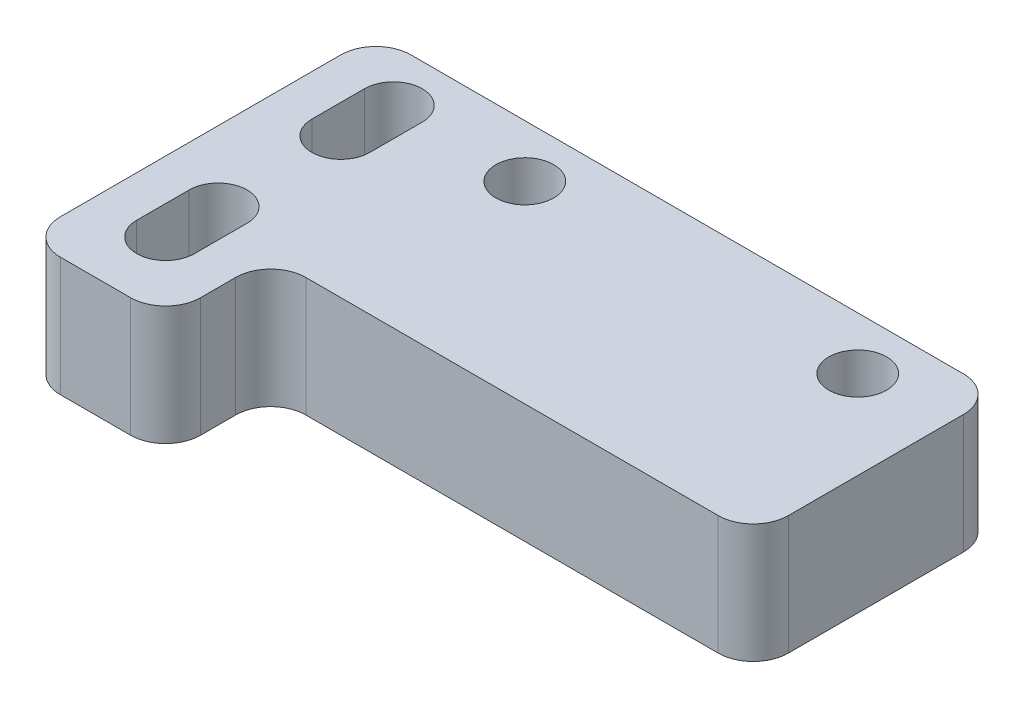
SolidWorks part; units mm, degrees
ref_plane "Front Plane" through (0, 0, 0) normal (0, 0, 1) x (1, 0, 0)
ref_plane "Top Plane" through (0, 0, 0) normal (0, 1, 0) x (1, 0, 0)
ref_plane "Right Plane" through (0, 0, 0) normal (1, 0, 0) x (0, 0, -1)
sketch "Sketch1" plane through (0, 0, 0) normal (0, 0, 1) x (1, 0, 0)
  line L0 (0, 3.6) -> (0, 0) construction
  line L1 (-13.77, -3.4) -> (13.77, -3.4)
  line L2 (-13.77, -3.4) -> (-13.77, 3.4)
  line L3 (-13.77, 3.4) -> (13.77, 3.4)
  line L4 (13.77, -3.4) -> (13.77, 3.4)
  line L5 (-13.77, -3.4) -> (13.77, 3.4) construction
  line L6 (-13.77, 3.4) -> (13.77, -3.4) construction
  circle A0 centre (0, 3.6) radius 7.6 construction
  point P0 (0, 0)
  dimension "D3" = 15.2
  dimension "D1" = 7
  dimension "D2" = 0.2
  dimension "D4" = 27.54
extrude "Boss-Extrude1" add sketch "Sketch1" along normal blind 8 contours A0 L3 L2 L1 L4
sketch "Sketch4" plane through (0, 0, 0) normal (0, 0, -1) x (-1, 0, 0)
  line L8 (-13.77, -3.4) -> (13.77, -3.4)
  line L9 (13.77, -3.4) -> (13.77, 3.4)
  line L10 (13.77, 3.4) -> (-13.77, 3.4)
  line L11 (-13.77, 3.4) -> (-13.77, -3.4)
  line L12 (-13.77, -3.4) -> (13.77, -3.4)
  line L13 (13.77, -3.4) -> (13.77, 3.4)
  line L14 (13.77, 3.4) -> (-13.77, 3.4)
  line L15 (-13.77, 3.4) -> (-13.77, -3.4)
  dimension "D1" = 0
extrude "Boss-Extrude2" add sketch "Sketch4" along normal blind 6
sketch "Sketch3" plane through (0, -3.4, 0) normal (0, -1, 0) x (1, 0, 0)
  line L0 (8.73, -3) -> (-10.27, -3) construction
  line L1 (13.77, -6) -> (-13.77, -6) construction
  line L2 (-13.77, 8) -> (-13.77, -6) construction
  arc A2 (7.13, 1) -> (10.33, 1) centre (8.73, -3) ccw construction
  arc A3 (-11.6208, 1) -> (-8.8261, 0.9674) centre (-10.27, -3) ccw construction
  circle A4 centre (8.73, -3) radius 1.65
  circle A5 centre (-10.27, -3) radius 1.65
  dimension "D1" = 3.3
  dimension "D2" = 19
  dimension "D3" = 3
  dimension "D4" = 3.5
extrude "Cut-Extrude2" cut sketch "Sketch3" against normal through all both and the other way through all
sketch "Sketch7" plane through (0, 3.4, 0) normal (0, 1, 0) x (1, 0, 0)
  line L0 (-17.77, 3) -> (-17.77, 0) construction
  line L1 (-13.77, 6) -> (-21.77, 6)
  line L2 (-13.77, 6) -> (-13.77, -14)
  line L3 (-13.77, -14) -> (-21.77, -14)
  line L4 (-21.77, 6) -> (-21.77, -14)
  line L5 (-16.12, 3) -> (-16.12, 0)
  line L6 (-19.42, 3) -> (-19.42, 0)
  line L7 (-17.77, -7) -> (-17.77, -10) construction
  line L8 (-16.12, -7) -> (-16.12, -10)
  line L9 (-19.42, -7) -> (-19.42, -10)
  line L10 (-17.77, -8.5) -> (-17.77, -14) construction
  line L11 (-17.77, -8.5) -> (-17.77, 1.5) construction
  arc A0 (-16.12, 3) -> (-19.42, 3) centre (-17.77, 3) ccw
  arc A1 (-19.42, 0) -> (-16.12, 0) centre (-17.77, 0) ccw
  arc A2 (-16.12, -7) -> (-19.42, -7) centre (-17.77, -7) ccw
  arc A3 (-19.42, -10) -> (-16.12, -10) centre (-17.77, -10) ccw
  point P7 (-17.77, 1.5)
  point P12 (-17.77, -8.5)
  dimension "D6" = 3.3
  dimension "D1" = 8
  dimension "D2" = 20
  dimension "D3" = 3
  dimension "D4" = 4
  dimension "D5" = 10
extrude "Boss-Extrude3" add sketch "Sketch7" against normal up to surface (6.8 mm away) up to face at (8.73, -3.4, -1.35)
fillet "Fillet1" radius 2 6 edges at (-13.77, 0, 8) (-13.77, 0, 14) (-21.77, 0, 14) (-21.77, 0, -6) (13.77, 0, -6) (13.77, 0, 8)
